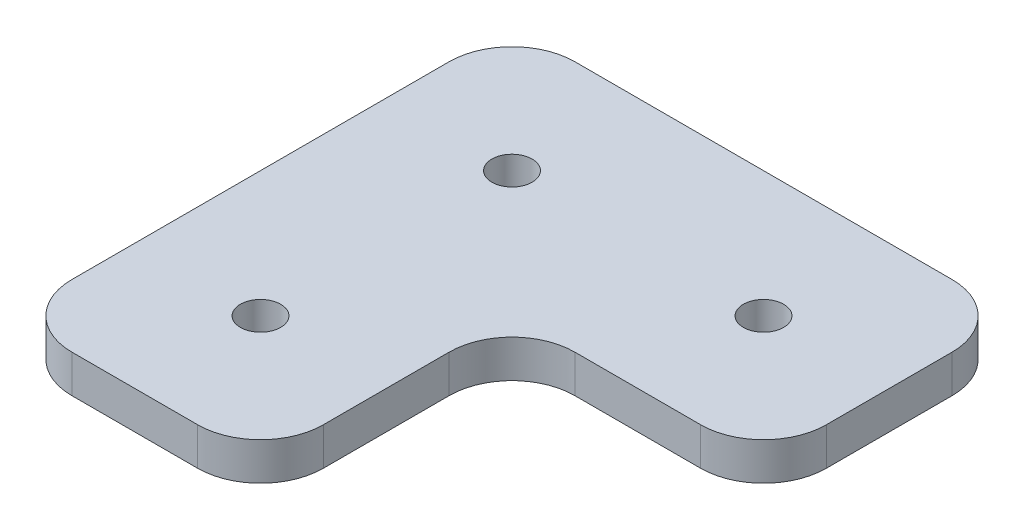
SolidWorks part; units mm, degrees
material "Thornel Mat VMA"
ref_plane "前视基准面" through (0, 0, 0) normal (0, 0, 1) x (1, 0, 0)
ref_plane "上视基准面" through (0, 0, 0) normal (0, 1, 0) x (1, 0, 0)
ref_plane "右视基准面" through (0, 0, 0) normal (1, 0, 0) x (0, 0, -1)
other "Configuration Table"
sketch "草图1" plane through (0, 0, 0) normal (0, 1, 0) x (1, 0, 0)
  line L0 (0, 0) -> (0, 40)
  line L1 (0, 40) -> (40, 40)
  line L2 (40, 40) -> (40, 20)
  line L4 (40, 20) -> (20, 20)
  line L5 (20, 20) -> (20, 0)
  line L6 (0, 0) -> (20, 0)
  circle A13 centre (30, 30) radius 1.6
  circle A14 centre (10, 30) radius 1.6
  circle A15 centre (10, 10) radius 1.6
  dimension "D8" = 10
  dimension "D5" = 3.2
  dimension "D6" = 3.2
  dimension "D7" = 3.2
  dimension "D1" = 20
  dimension "D2" = 20
  dimension "D3" = 40
  dimension "D4" = 20
  dimension "D10" = 10
  dimension "D11" = 20
  dimension "D12" = 10
  dimension "D13" = 20
  dimension "D9" = 10
extrude "凸台-拉伸1" add sketch "草图1" along normal blind 3
fillet "圆角1" radius 5 6 edges at (0, 1.5, 0) (20, 1.5, 0) (40, 1.5, -20) (40, 1.5, -40) (0, 1.5, -40) (20, 1.5, -20)
